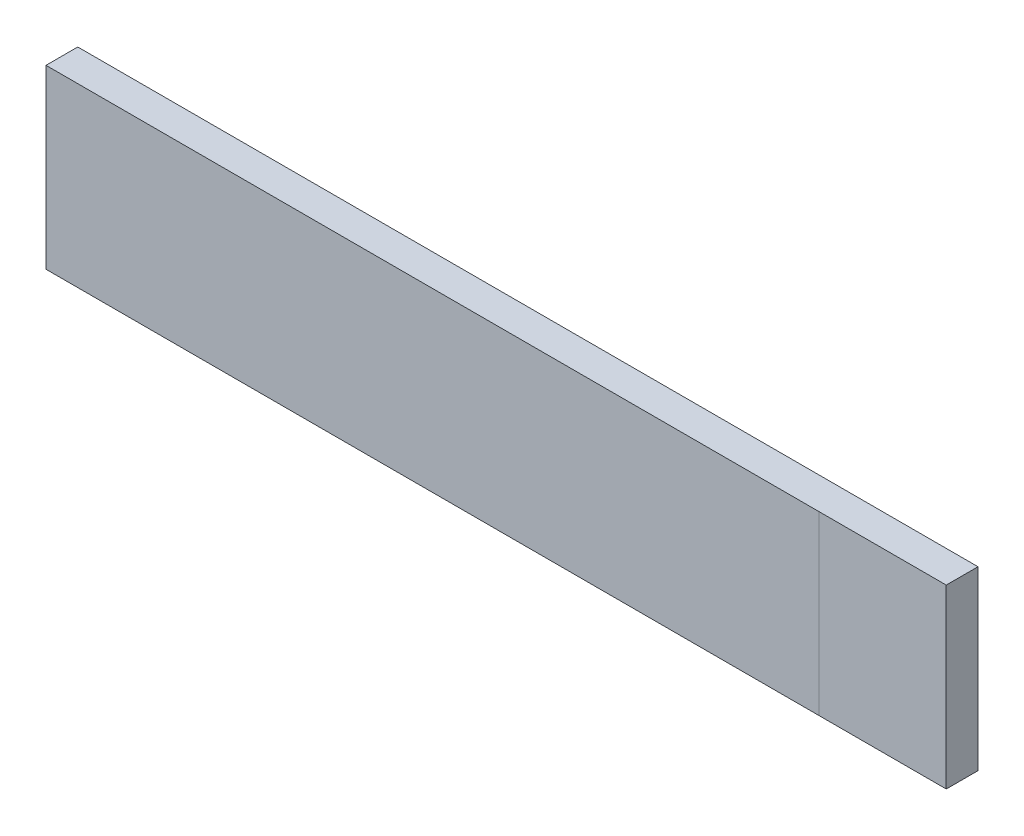
SolidWorks part; units mm, degrees
material "AISI 304"
ref_plane "前视基准面" through (0, 0, 0) normal (0, 0, 1) x (1, 0, 0)
ref_plane "上视基准面" through (0, 0, 0) normal (0, 1, 0) x (1, 0, 0)
ref_plane "右视基准面" through (0, 0, 0) normal (1, 0, 0) x (0, 0, -1)
sketch "草图1" plane through (0, 0, 0) normal (0, 0, 1) x (1, 0, 0)
  line L0 (-141.7333, -27.8112) -> (141.7333, -27.8112)
  line L1 (-141.7333, -27.8112) -> (-141.7333, 27.8112)
  line L2 (141.7333, -27.8112) -> (141.7333, 27.8112)
  line L3 (-141.7333, 27.8112) -> (141.7333, 27.8112)
  line L4 (141.7333, 0) -> (-141.7333, 0) construction
  line L5 (0, -27.8112) -> (0, 27.8112) construction
  point P1 (0, 0)
extrude "凸台-拉伸1" add sketch "草图1" along normal blind 10
sketch "草图2" plane through (0, 0, 10) normal (0, 0, 1) x (1, 0, 0)
  line L0 (101.7333, 27.8112) -> (101.7333, -30.7464)
  line L1 (141.7333, 27.8112) -> (-141.7333, 27.8112) construction
  line L2 (141.7333, -27.8112) -> (141.7333, 27.8112) construction
  dimension "D1" = 40
split line "分割线1"
